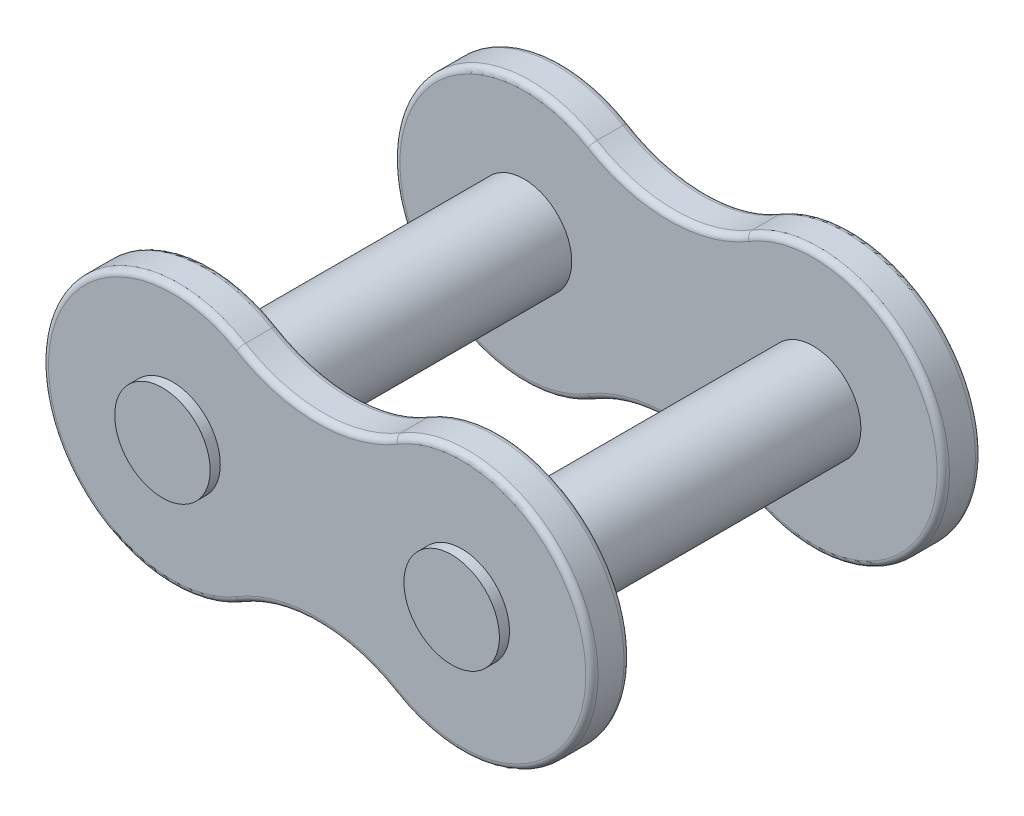
SolidWorks part; units mm, degrees
ref_plane "Front Plane" through (0, 0, 0) normal (0, 0, 1) x (1, 0, 0)
ref_plane "Top Plane" through (0, 0, 0) normal (0, 1, 0) x (1, 0, 0)
ref_plane "Right Plane" through (0, 0, 0) normal (1, 0, 0) x (0, 0, -1)
sketch "Sketch1" plane through (0, 0, 0) normal (0, 0, 1) x (1, 0, 0)
  line L0 (0, 0) -> (0, 10.0319) construction
  line L1 (0, 0) -> (-6, 0) construction
  arc A0 (-3.2217, 4.6305) -> (-3.2217, -4.6305) centre (-6, 0) ccw
  circle A1 centre (-6, 0) radius 1.98
  circle A2 centre (6, 0) radius 1.98
  arc A3 (3.2217, 4.6305) -> (3.2217, -4.6305) centre (6, 0) cw
  arc A4 (3.2217, 4.6305) -> (-3.2217, 4.6305) centre (0, 10) cw
  arc A5 (3.2217, -4.6305) -> (-3.2217, -4.6305) centre (0, -10) ccw
  point P12 (0, 0)
  dimension "D1" = 10.8
  dimension "D2" = 3.96
  dimension "D4" = 6.2619
  dimension "D3" = 6
extrude "Boss-Extrude1" add sketch "Sketch1" along normal blind 1.5875
sketch "Sketch2" plane through (0, 0, 0) normal (0, 0, -1) x (-1, 0, 0)
  circle A0 centre (-6, 0) radius 1.98
extrude "Boss-Extrude3" add sketch "Sketch2" along normal blind 15 and the other way blind 2.0075
mirror "Mirror1" about plane through (0, 0, 0) normal (1, 0, 0) of "Boss-Extrude3"
ref_plane "Plane4" through (0, 0, -6.4962) normal (0, 0, -1) x (-1, 0, 0)
mirror "Mirror2" about plane through (0, 0, -6.4962) normal (0, 0, -1) of "Boss-Extrude1"
fillet "Fillet1" radius 0.254 16 edges at (11.4, 0, 1.5875) (0, -3.7381, 1.5875) (-11.4, 0, 1.5875) (11.4, 0, 0) (0, -3.7381, 0) (-11.4, 0, 0) (11.4, 0, -12.9925) (0, -3.7381, -12.9925) (-11.4, 0, -12.9925) (11.4, 0, -14.58) (0, -3.7381, -14.58) (-11.4, 0, -14.58) (0, 3.7381, 1.5875) (0, 3.7381, 0) (0, 3.7381, -12.9925) (0, 3.7381, -14.58)
